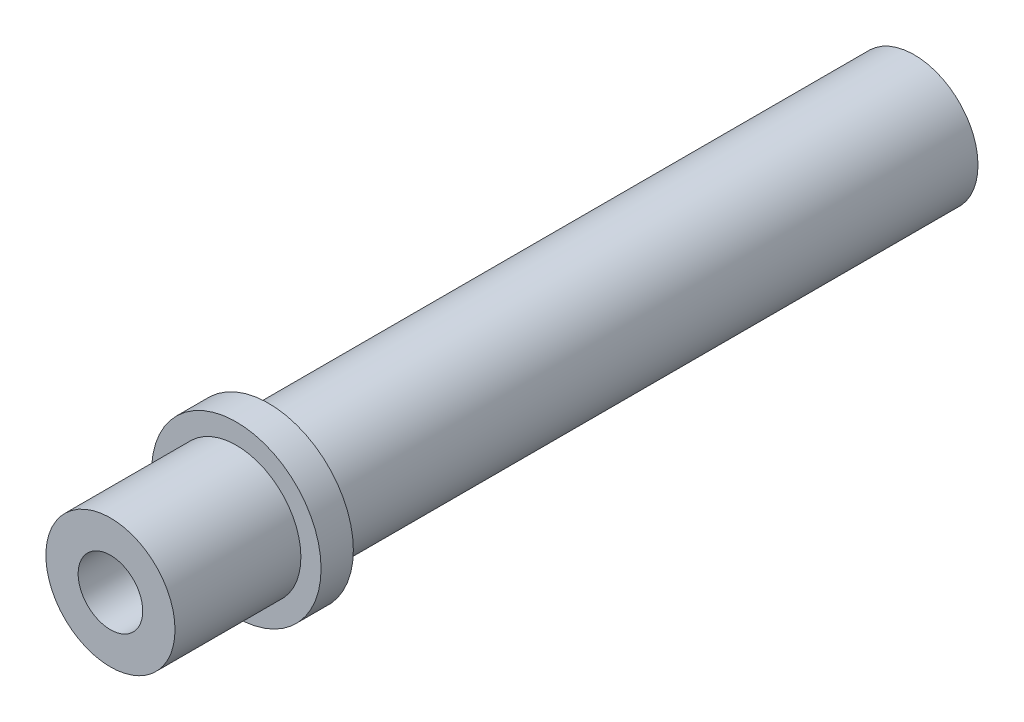
SolidWorks part; units mm, degrees
ref_plane "Front Plane" through (0, 0, 0) normal (0, 0, 1) x (1, 0, 0)
ref_plane "Top Plane" through (0, 0, 0) normal (0, 1, 0) x (1, 0, 0)
ref_plane "Right Plane" through (0, 0, 0) normal (1, 0, 0) x (0, 0, -1)
sketch "S01 - Printable sliding pin - 7.90 mm" plane through (0, 0, 0) normal (0, 0, 1) x (1, 0, 0)
  circle A0 centre (0, 0) radius 3.95
extrude "01 - Printable sliding pin - 7.90 mm" add sketch "S01 - Printable sliding pin - 7.90 mm" along normal blind 40
sketch "S02 - Recessed load shoulder" plane through (0, 0, 0) normal (0, 0, 1) x (1, 0, 0)
  circle A0 centre (0, 0) radius 5.25
extrude "02 - Recessed load shoulder" add sketch "S02 - Recessed load shoulder" along normal blind 2 from offset 40
sketch "S03 - Locating pilot through swing arm" plane through (0, 0, 0) normal (0, 0, 1) x (1, 0, 0)
  circle A0 centre (0, 0) radius 4
extrude "03 - Locating pilot through swing arm" add sketch "S03 - Locating pilot through swing arm" along normal blind 7.8 from offset 42
sketch "S04 - M3 heat-set pocket in supported root" plane through (0, 0, 0) normal (0, 0, 1) x (1, 0, 0)
  circle A0 centre (0, 0) radius 2
extrude "04 - M3 heat-set pocket in supported root" cut sketch "S04 - M3 heat-set pocket in supported root" along normal blind 7.3 from offset 42.6
